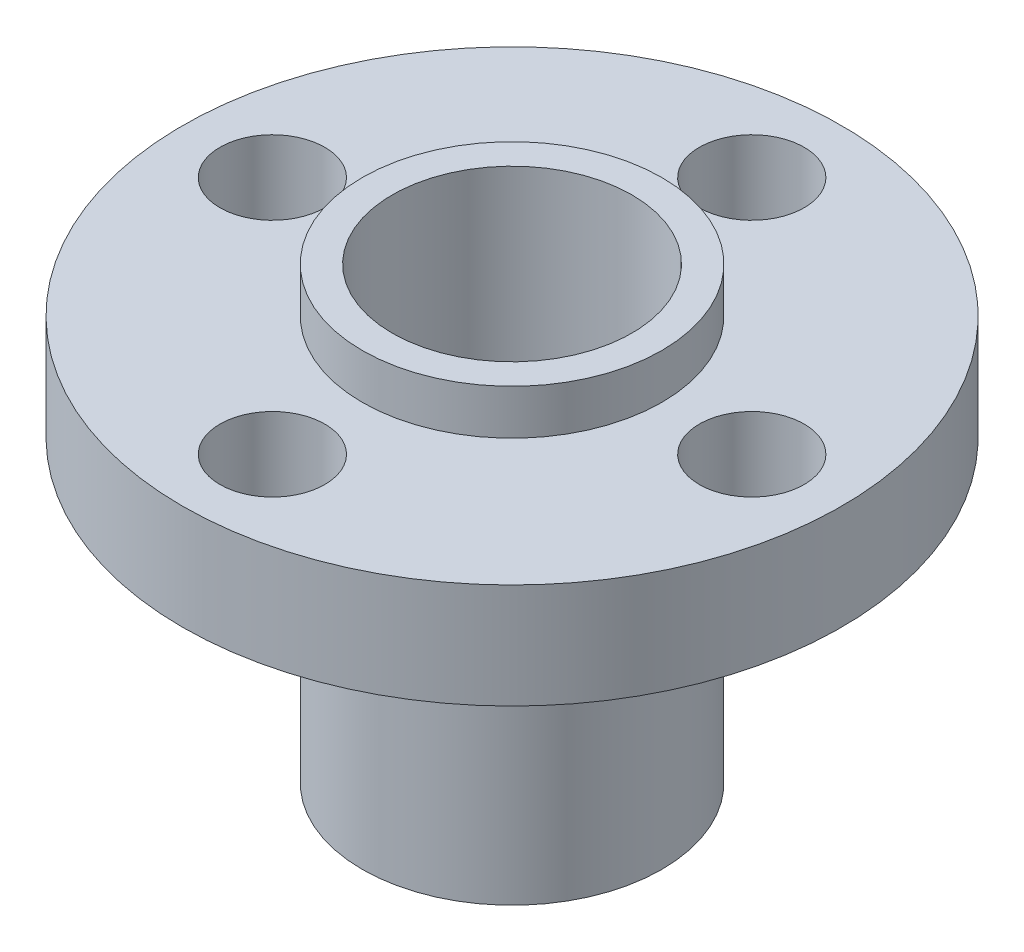
SolidWorks part; units mm, degrees
material "锰青铜"
ref_plane "前视基准面" through (0, 0, 0) normal (0, 0, 1) x (1, 0, 0)
ref_plane "上视基准面" through (0, 0, 0) normal (0, 1, 0) x (1, 0, 0)
ref_plane "右视基准面" through (0, 0, 0) normal (1, 0, 0) x (0, 0, -1)
sketch "草图1" plane through (0, 0, 0) normal (0, 1, 0) x (1, 0, 0)
  circle A0 centre (0, 0) radius 4
  circle A1 centre (0, 0) radius 5
  dimension "D1" = 8
  dimension "D2" = 10
extrude "凸台-拉伸1" add sketch "草图1" along normal blind 10
ref_plane "基准面1" through (0, 10, 0) normal (0, 1, 0) x (1, 0, 0)
sketch "草图2" plane through (0, 10, 0) normal (0, 1, 0) x (1, 0, 0)
  circle A0 centre (0, 0) radius 4
  circle A1 centre (0, 0) radius 11
  dimension "D1" = 22
extrude "凸台-拉伸2" add sketch "草图2" along normal blind 3.5
ref_plane "基准面2" through (0, 13.5, 0) normal (0, 1, 0) x (1, 0, 0)
sketch "草图3" plane through (0, 13.5, 0) normal (0, 1, 0) x (1, 0, 0)
  circle A0 centre (0, 0) radius 4
  circle A1 centre (0, 0) radius 5
  dimension "D1" = 8
  dimension "D2" = 10
extrude "凸台-拉伸3" add sketch "草图3" along normal blind 1.5
sketch "草图4" plane through (0, 13.5, 0) normal (0, 1, 0) x (1, 0, 0)
  circle A0 centre (0, 0) radius 8 construction
  circle A1 centre (-8, 0) radius 1.75
  circle A2 centre (0, 8) radius 1.75
  circle A3 centre (8, 0) radius 1.75
  circle A4 centre (0, -8) radius 1.75
  point P14 (0, 0)
  dimension "D1" = 16
  dimension "D2" = 3.5
  dimension "D3" = 4
extrude "切除-拉伸1" cut sketch "草图4" against normal through all
